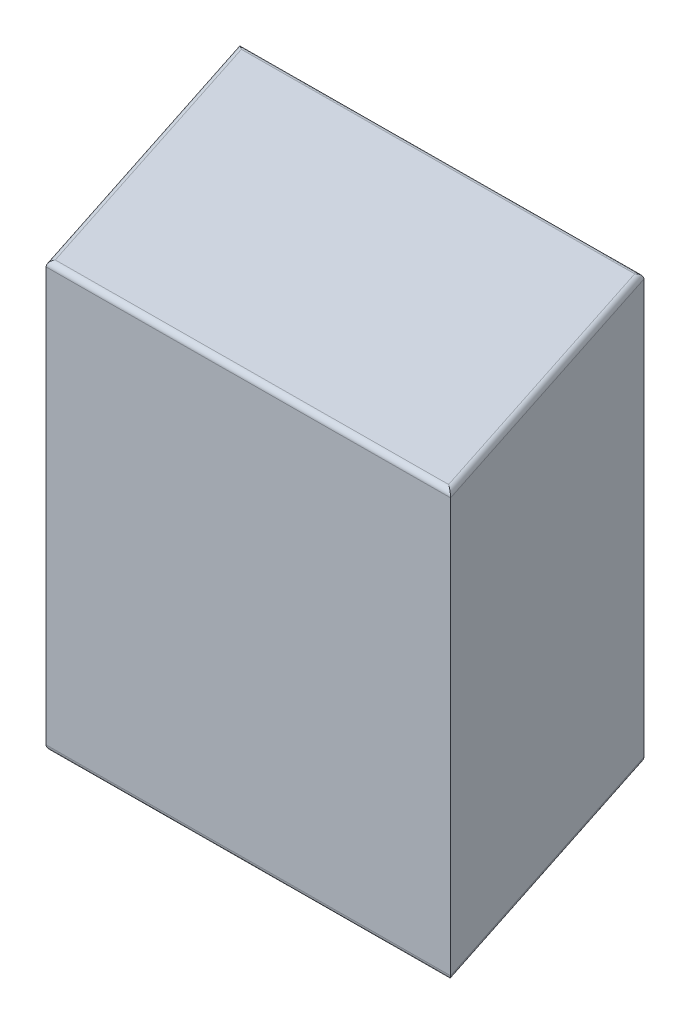
SolidWorks part; units mm, degrees
ref_plane "Front Plane" through (0, 0, 0) normal (1, 0, 0) x (0, 1, 0)
ref_plane "Top Plane" through (0, 0, 0) normal (0, 0, 1) x (0, 1, 0)
ref_plane "Right Plane" through (0, 0, 0) normal (0, 1, 0) x (-1, 0, 0)
sketch "Sketch1" plane through (0, 0, 0) normal (0, 1, 0) x (-1, 0, 0)
  line L0 (-0.3769, 0.0837) -> (8.3632, -26.8667)
  line L1 (8.3632, -26.8667) -> (-29.5375, -27.0837)
  line L2 (-29.5375, -27.0837) -> (-38.2776, -0.1333)
  line L3 (-38.2776, -0.1333) -> (-0.3769, 0.0837)
extrude "Boss-Extrude1" add sketch "Sketch1" along normal blind 40
fillet "Fillet1" radius 0.5 8 edges at (19.3272, 0, -0.0248) (33.9075, 0, -13.6085) (10.5871, 0, -26.9752) (-3.9932, 0, -13.3915) (19.3272, 40, -0.0248) (33.9075, 40, -13.6085) (10.5871, 40, -26.9752) (-3.9932, 40, -13.3915)
